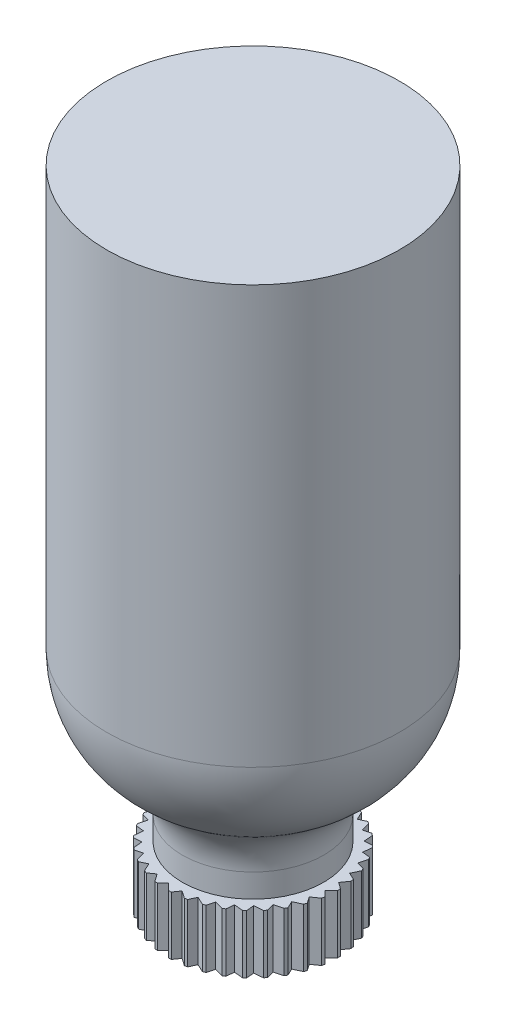
SolidWorks part; units mm, degrees
ref_plane "Front Plane" through (0, 0, 0) normal (0, 0, 1) x (1, 0, 0)
ref_plane "Top Plane" through (0, 0, 0) normal (0, 1, 0) x (1, 0, 0)
ref_plane "Right Plane" through (0, 0, 0) normal (1, 0, 0) x (0, 0, -1)
sketch "Sketch1" plane through (0, 0, 0) normal (0, 1, 0) x (1, 0, 0)
  line L0 (-14.5, 0) -> (-13.4131, 1.0869)
  line L1 (-13.4131, 1.0869) -> (-14.3571, 2.0308)
  line L2 (-14.2797, 2.5179) -> (-13.0206, 3.3995)
  line L3 (-13.0206, 3.3995) -> (-13.7863, 4.493)
  line L4 (-13.6255, 4.9593) -> (-12.2325, 5.6089)
  line L5 (-12.2325, 5.6089) -> (-12.7967, 6.8187)
  line L6 (-12.5574, 7.25) -> (-11.0727, 7.6478)
  line L7 (-11.0727, 7.6478) -> (-11.4182, 8.9373)
  line L8 (-11.1076, 9.3204) -> (-9.5764, 9.4544)
  line L9 (-9.5764, 9.4544) -> (-9.6928, 10.7842)
  line L10 (-9.3204, 11.1076) -> (-7.7892, 10.9737)
  line L11 (-7.7892, 10.9737) -> (-7.6729, 12.3035)
  line L12 (-7.25, 12.5574) -> (-5.7653, 12.1596)
  line L13 (-5.7653, 12.1596) -> (-5.4198, 13.449)
  line L14 (-4.9593, 13.6255) -> (-3.5663, 12.976)
  line L15 (-3.5663, 12.976) -> (-3.0021, 14.1858)
  line L16 (-2.5179, 14.2797) -> (-1.2588, 13.3981)
  line L17 (-1.2588, 13.3981) -> (-0.4931, 14.4916)
  line L18 (0, 14.5) -> (1.0869, 13.4131)
  line L19 (1.0869, 13.4131) -> (2.0308, 14.3571)
  line L20 (2.5179, 14.2797) -> (3.3995, 13.0206)
  line L21 (3.3995, 13.0206) -> (4.493, 13.7863)
  line L22 (4.9593, 13.6255) -> (5.6089, 12.2325)
  line L23 (5.6089, 12.2325) -> (6.8187, 12.7967)
  line L24 (7.25, 12.5574) -> (7.6478, 11.0727)
  line L25 (7.6478, 11.0727) -> (8.9373, 11.4182)
  line L26 (9.3204, 11.1076) -> (9.4544, 9.5764)
  line L27 (9.4544, 9.5764) -> (10.7842, 9.6928)
  line L28 (11.1076, 9.3204) -> (10.9737, 7.7892)
  line L29 (10.9737, 7.7892) -> (12.3035, 7.6729)
  line L30 (12.5574, 7.25) -> (12.1596, 5.7653)
  line L31 (12.1596, 5.7653) -> (13.449, 5.4198)
  line L32 (13.6255, 4.9593) -> (12.976, 3.5663)
  line L33 (12.976, 3.5663) -> (14.1858, 3.0021)
  line L34 (14.2797, 2.5179) -> (13.3981, 1.2588)
  line L35 (13.3981, 1.2588) -> (14.4916, 0.4931)
  line L36 (14.5, 0) -> (13.4131, -1.0869)
  line L37 (13.4131, -1.0869) -> (14.3571, -2.0308)
  line L38 (14.2797, -2.5179) -> (13.0206, -3.3995)
  line L39 (13.0206, -3.3995) -> (13.7863, -4.493)
  line L40 (13.6255, -4.9593) -> (12.2325, -5.6089)
  line L41 (12.2325, -5.6089) -> (12.7967, -6.8187)
  line L42 (12.5574, -7.25) -> (11.0727, -7.6478)
  line L43 (11.0727, -7.6478) -> (11.4182, -8.9373)
  line L44 (11.1076, -9.3204) -> (9.5764, -9.4544)
  line L45 (9.5764, -9.4544) -> (9.6928, -10.7842)
  line L46 (9.3204, -11.1076) -> (7.7892, -10.9737)
  line L47 (7.7892, -10.9737) -> (7.6729, -12.3035)
  line L48 (7.25, -12.5574) -> (5.7653, -12.1596)
  line L49 (5.7653, -12.1596) -> (5.4198, -13.449)
  line L50 (4.9593, -13.6255) -> (3.5663, -12.976)
  line L51 (3.5663, -12.976) -> (3.0021, -14.1858)
  line L52 (2.5179, -14.2797) -> (1.2588, -13.3981)
  line L53 (1.2588, -13.3981) -> (0.4931, -14.4916)
  line L54 (0, -14.5) -> (-1.0869, -13.4131)
  line L55 (-1.0869, -13.4131) -> (-2.0308, -14.3571)
  line L56 (-2.5179, -14.2797) -> (-3.3995, -13.0206)
  line L57 (-3.3995, -13.0206) -> (-4.493, -13.7863)
  line L58 (-4.9593, -13.6255) -> (-5.6089, -12.2325)
  line L59 (-5.6089, -12.2325) -> (-6.8187, -12.7967)
  line L60 (-7.25, -12.5574) -> (-7.6478, -11.0727)
  line L61 (-7.6478, -11.0727) -> (-8.9373, -11.4182)
  line L62 (-9.3204, -11.1076) -> (-9.4544, -9.5764)
  line L63 (-9.4544, -9.5764) -> (-10.7842, -9.6928)
  line L64 (-11.1076, -9.3204) -> (-10.9737, -7.7892)
  line L65 (-10.9737, -7.7892) -> (-12.3035, -7.6729)
  line L66 (-12.5574, -7.25) -> (-12.1596, -5.7653)
  line L67 (-12.1596, -5.7653) -> (-13.449, -5.4198)
  line L68 (-13.6255, -4.9593) -> (-12.976, -3.5663)
  line L69 (-12.976, -3.5663) -> (-14.1858, -3.0021)
  line L70 (-14.2797, -2.5179) -> (-13.3981, -1.2588)
  line L71 (-13.3981, -1.2588) -> (-14.4916, -0.4931)
  circle A0 centre (0, 0) radius 14.5
  point P113 (0, 0)
  dimension "D1" = 29
  dimension "D2" = 36
extrude "Boss-Extrude1" add sketch "Sketch1" along normal mid plane 10 contours L54 A0 L53 L52 L51 L50 L49 L48 L47 L46 L45 L44 L43 L42 L41 L40 L39 L38 L37 L36 L35 L34 L33 L32 L31 L30 L29 L28 L27 L26 L25 L24 L23 L22 L21
sketch "Sketch2" plane through (0, 0, 0) normal (1, 0, 0) x (0, 0, -1)
  line L0 (12.1049, 4.765) -> (12.1049, 19.027)
  line L1 (22.1049, 19.027) -> (25.0619, 19.027)
  line L2 (25.0619, 19.027) -> (25.0619, 105.2644)
  line L3 (25.0619, 105.2644) -> (0, 105.2644)
  line L4 (0, 105.2644) -> (0, 0)
  line L5 (0, 0) -> (12.1049, 0)
  line L6 (12.1049, 0) -> (12.1049, 9.027)
  arc A0 (22.1049, 19.027) -> (12.1049, 9.027) centre (22.1049, 9.027) ccw
  dimension "D1" = 10
revolve "Revolve1" add sketch "Sketch2" angle 360 about L4
fillet "Fillet1" radius 20 1 edges at (0, 19.027, 25.0619)
